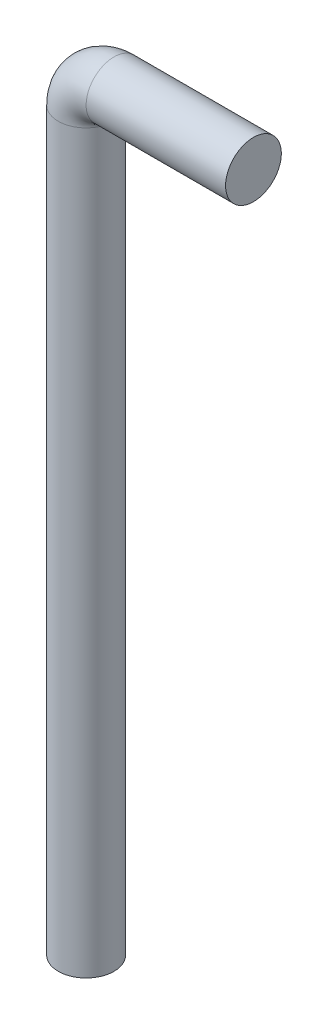
SolidWorks part; units mm, degrees
ref_plane "前视基准面" through (0, 0, 0) normal (0, 0, 1) x (1, 0, 0)
ref_plane "上视基准面" through (0, 0, 0) normal (0, 1, 0) x (1, 0, 0)
ref_plane "右视基准面" through (0, 0, 0) normal (1, 0, 0) x (0, 0, -1)
sketch "草图2" plane through (0, 0, 0) normal (0, 1, 0) x (1, 0, 0)
  circle A0 centre (0, 0) radius 2.5
  dimension "D1" = 5
extrude "凸台-拉伸1" add sketch "草图2" along normal blind 66
sketch "草图5" plane through (0, 0, 0) normal (0, 0, 1) x (1, 0, 0)
  line L0 (0, -12.2651) -> (0, 76.2981) construction
  line L1 (-3.9174, 63.1232) -> (9.7556, 63.1232) construction
  line L2 (2.5, 64.831) -> (2.5, 69.9192) construction
  line L3 (2.5, 0) -> (2.5, 66) construction
  line L4 (2.5, 66) -> (-2.5, 66) construction
  line L5 (2.5, 68.5) -> (15, 68.5)
  arc A0 (2.5, 68.5) -> (0, 66) centre (2.5, 66) ccw
  dimension "D1" = 15
sketch "草图6" plane through (0, 66, 0) normal (0, 1, 0) x (1, 0, 0)
  circle A0 centre (0, 0) radius 2.5 construction
  circle A1 centre (0, 0) radius 2.5
sweep "扫描1" add profiles "草图6" path "草图5"
